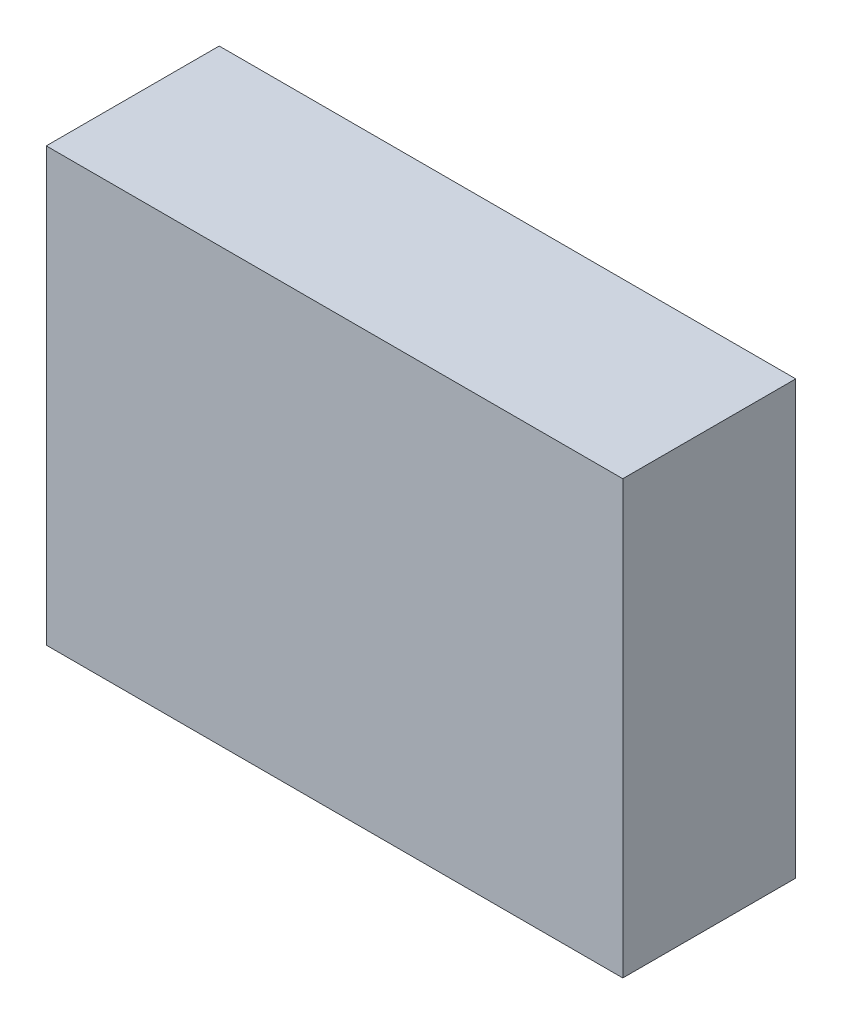
SolidWorks part; units mm, degrees
ref_plane "前视基准面" through (0, 0, 0) normal (0, 0, 1) x (1, 0, 0)
ref_plane "上视基准面" through (0, 0, 0) normal (0, 1, 0) x (1, 0, 0)
ref_plane "右视基准面" through (0, 0, 0) normal (1, 0, 0) x (0, 0, -1)
other "Configuration Table"
sketch "草图1" plane through (0, 0, 0) normal (0, 0, 1) x (1, 0, 0)
  line L1 (-10, 7.5) -> (10, 7.5)
  line L2 (-10, 7.5) -> (-10, -7.5)
  line L3 (-10, -7.5) -> (10, -7.5)
  line L4 (10, 7.5) -> (10, -7.5)
  line L5 (-10, 7.5) -> (10, -7.5) construction
  line L6 (-10, -7.5) -> (10, 7.5) construction
  point P0 (0, 0)
  point P5 (0, 0)
  dimension "D1" = 20
  dimension "D2" = 15
extrude "凸台-拉伸1" add sketch "草图1" along normal mid plane 6
